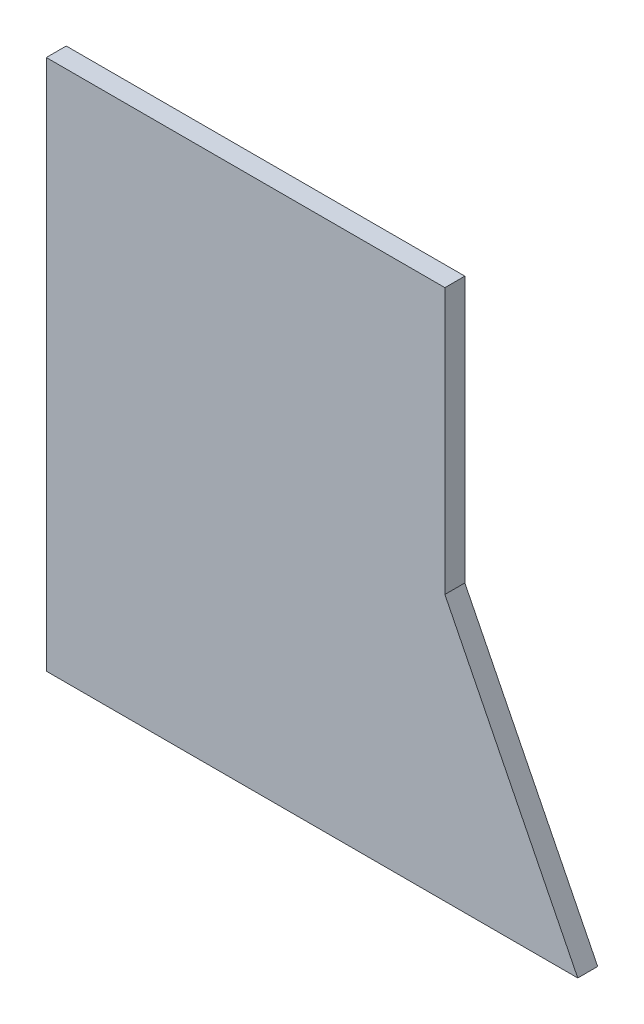
SolidWorks part; units mm, degrees
ref_plane "Front Plane" through (0, 0, 0) normal (0, 0, 1) x (1, 0, 0)
ref_plane "Top Plane" through (0, 0, 0) normal (0, 1, 0) x (1, 0, 0)
ref_plane "Right Plane" through (0, 0, 0) normal (1, 0, 0) x (0, 0, -1)
sketch "Sketch1" plane through (0, 0, 0) normal (0, 0, 1) x (1, 0, 0)
  line L0 (0.3, 0) -> (0.5, -0.4)
  line L1 (-0.3, 0.4) -> (0.3, 0.4)
  line L2 (-0.3, 0.4) -> (-0.3, -0.4)
  line L3 (-0.3, -0.4) -> (0.3, -0.4)
  line L4 (0.3, 0.4) -> (0.3, 0)
  line L5 (-0.3, 0.4) -> (0.3, -0.4) construction
  line L6 (-0.3, -0.4) -> (0.3, 0.4) construction
  line L7 (0.5, -0.4) -> (0.3, -0.4)
  point P0 (0, 0)
  point P15 (0, 0)
  dimension "D1" = 0.8
  dimension "D2" = 0.6
  dimension "D3" = 0.2
extrude "Boss-Extrude2" add sketch "Sketch1" along normal mid plane 0.03
